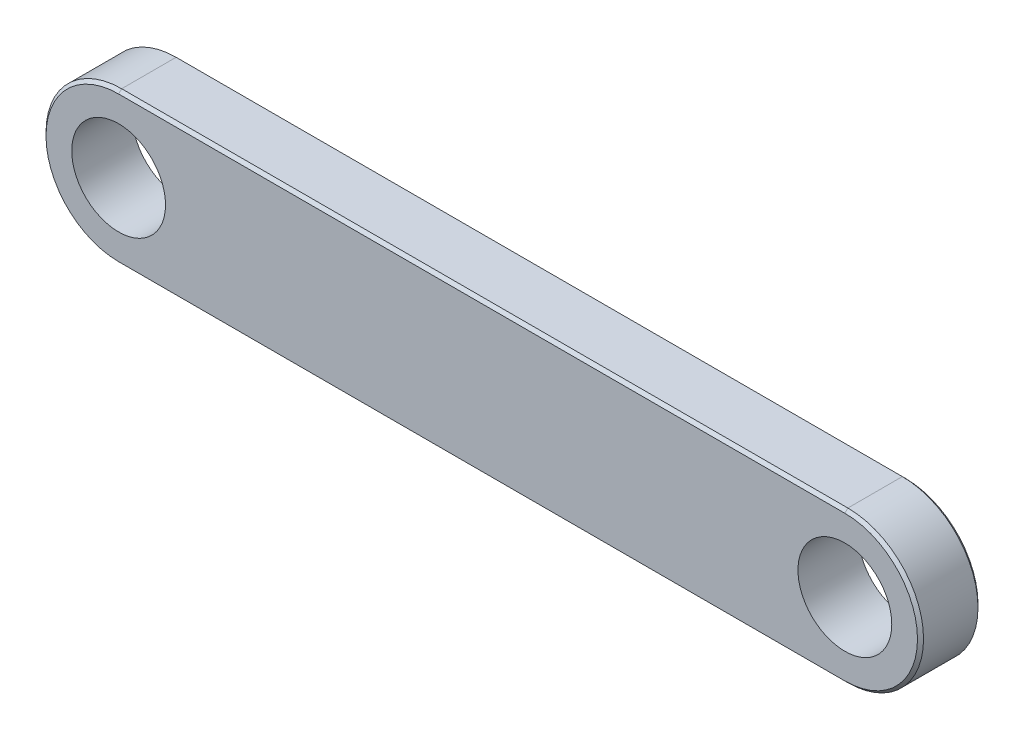
SolidWorks part; units mm, degrees
ref_plane "Front Plane" through (0, 0, 0) normal (0, 0, 1) x (1, 0, 0)
ref_plane "Top Plane" through (0, 0, 0) normal (0, 1, 0) x (1, 0, 0)
ref_plane "Right Plane" through (0, 0, 0) normal (1, 0, 0) x (0, 0, -1)
sketch "Sketch1" plane through (0, 0, 0) normal (0, 0, 1) x (1, 0, 0)
  line L0 (-11.9297, 0) -> (12.0703, 0) construction
  line L1 (-11.9297, 2.5) -> (12.0703, 2.5)
  line L2 (-11.9297, -2.5) -> (12.0703, -2.5)
  arc A0 (-11.9297, 2.5) -> (-11.9297, -2.5) centre (-11.9297, 0) ccw
  arc A1 (12.0703, -2.5) -> (12.0703, 2.5) centre (12.0703, 0) ccw
  circle A2 centre (12.0703, 0) radius 1.55
  circle A3 centre (-11.9297, 0) radius 1.55
  point P3 (0.0703, 0)
  dimension "D2" = 2.5
  dimension "D3" = 3.1
  dimension "D4" = 3.1
  dimension "D1" = 24
extrude "Boss-Extrude1" add sketch "Sketch1" along normal blind 2
chamfer "Chamfer1" distance 0.1 angle 45 8 edges at (0.0703, -2.5, 0) (14.5703, 0, 0) (-14.4297, 0, 0) (0.0703, 2.5, 0) (0.0703, -2.5, 2) (14.5703, 0, 2) (-14.4297, 0, 2) (0.0703, 2.5, 2)
